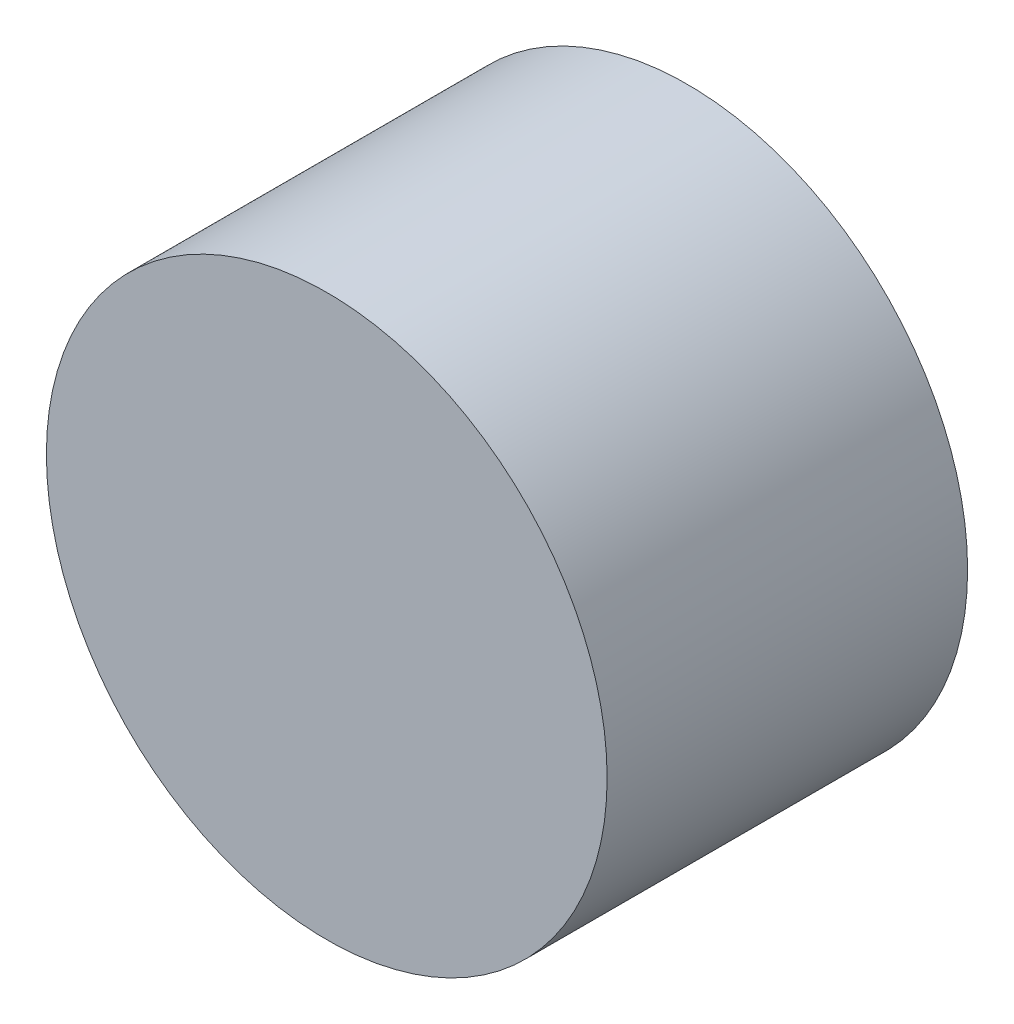
SolidWorks part; units mm, degrees
ref_plane "前视基准面" through (0, 0, 0) normal (0, 0, 1) x (1, 0, 0)
ref_plane "上视基准面" through (0, 0, 0) normal (0, 1, 0) x (1, 0, 0)
ref_plane "右视基准面" through (0, 0, 0) normal (1, 0, 0) x (0, 0, -1)
other "Configuration Table"
sketch "草图1" plane through (0, 0, 0) normal (0, 0, 1) x (1, 0, 0)
  circle A0 centre (0, 0) radius 14
extrude "凸台-拉伸1" add sketch "草图1" along normal blind 18
